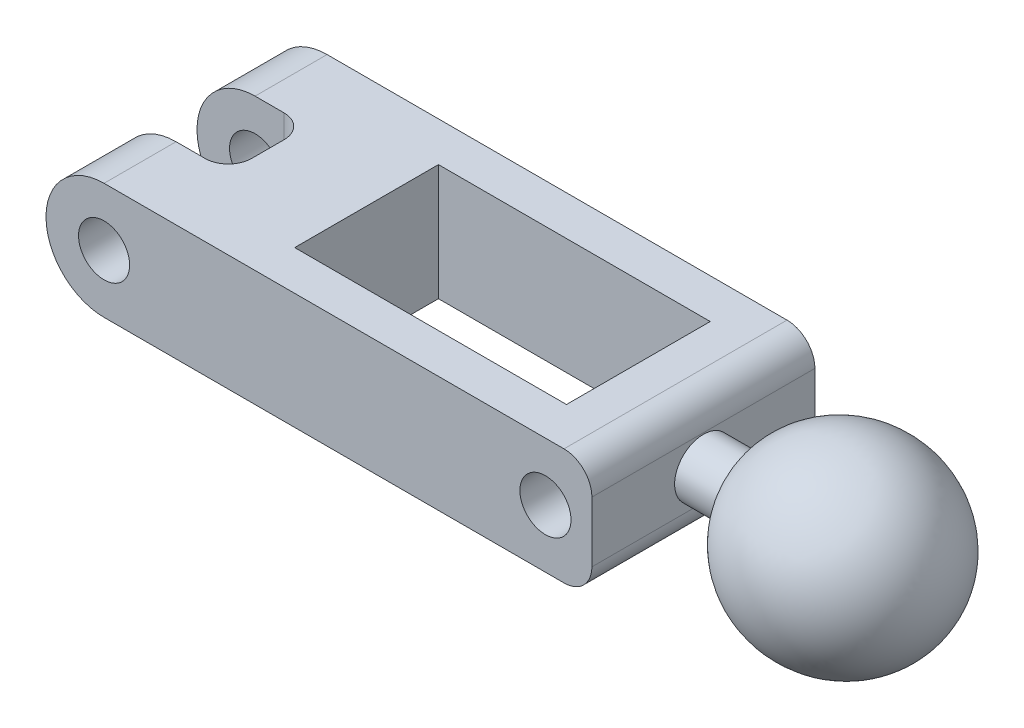
SolidWorks part; units mm, degrees
ref_plane "Front Plane" through (0, 0, 0) normal (0, 0, 1) x (1, 0, 0)
ref_plane "Top Plane" through (0, 0, 0) normal (0, 1, 0) x (1, 0, 0)
ref_plane "Right Plane" through (0, 0, 0) normal (1, 0, 0) x (0, 0, -1)
sketch "Sketch1" plane through (0, 0, 0) normal (0, 0, 1) x (1, 0, 0)
  line L0 (9.5, 0) -> (-9.5, 0) construction
  line L1 (9.5, -2.5) -> (-9.5, -2.5)
  line L2 (9.5, 2.5) -> (-9.5, 2.5)
  line L3 (9.5, 2.5) -> (9.5, -2.5) construction
  line L4 (9.5, 2.5) -> (10.3, 2.5)
  line L5 (11.5, 1.3) -> (11.5, -0.8015)
  line L6 (10.3, -2.5) -> (9.5, -2.5)
  line L9 (11.5, -0.8015) -> (11.5, -1.3)
  arc A1 (-9.5, 2.5) -> (-9.5, -2.5) centre (-9.5, 0) ccw
  circle A2 centre (-9.5, 0) radius 1.1
  circle A3 centre (9.5, 0) radius 1.1
  arc A4 (11.5, -1.3) -> (10.3, -2.5) centre (10.3, -1.3) cw
  arc A5 (10.3, 2.5) -> (11.5, 1.3) centre (10.3, 1.3) cw
  point P2 (0, 0)
  dimension "D1" = 2.5
  dimension "D3" = 2.2
  dimension "D5" = 1.2
  dimension "D2" = 19
  dimension "D4" = 21
extrude "Boss-Extrude1" add sketch "Sketch1" along normal mid plane 9.6
sketch "Sketch2" plane through (0, 0, 0) normal (0, 1, 0) x (1, 0, 0)
  line L0 (-12, 4.8) -> (-12, -4.8) construction
  line L1 (-12, 1.7) -> (-7.25, 1.7)
  line L2 (-12, 1.7) -> (-12, -1.7)
  line L3 (-12, -1.7) -> (-7.25, -1.7)
  line L4 (-7.25, 1.7) -> (-7.25, -1.7)
  line L5 (0, 0) -> (-14.5, 0) construction
  line L7 (-9.5, -4.8) -> (-9.5, 4.8) construction
  line L8 (8.7, 3.094) -> (-3, 3.094)
  line L9 (8.7, 3.094) -> (8.7, -3.094)
  line L10 (8.7, -3.094) -> (-3, -3.094)
  line L11 (-3, 3.094) -> (-3, -3.094)
  line L12 (8.7, 3.094) -> (-3, -3.094) construction
  line L13 (8.7, -3.094) -> (-3, 3.094) construction
  line L14 (-9.5, 4.8) -> (10.3, 4.8) construction
  line L15 (-8.4, 4.8) -> (-10.6, 4.8) construction
  point P9 (-7.25, 0)
  point P12 (2.85, 0)
  dimension "D1" = 4.25
  dimension "D2" = 2.25
  dimension "D3" = 18.2
  dimension "D4" = 7.894
  dimension "D5" = 3.1
extrude "Cut-Extrude1" cut sketch "Sketch2" against normal mid plane 9.6 contours L8 L11 L10 L9 | L1 L4 L3 L2
sketch "Sketch6" plane through (0, 0, 0) normal (0, 0, 1) x (1, 0, 0)
  line L0 (11.5, 1.3) -> (11.5, -1.3) construction
  line L3 (11.5, -1.24) -> (13.5, -1.24)
  line L6 (13.5, 0) -> (21.6962, 0) construction
  line L8 (0, 0) -> (3.0263, 0) construction
  line L9 (11.5, 0) -> (21.6962, 0)
  line L10 (11.5, 0) -> (11.5, -1.24)
  circle A1 centre (-9.5, 0) radius 1.1 construction
  ellipse E0 centre (17.5, -0.0284) end of major axis (21.6962, 0) minor radius 4 (13.5, -1.24) -> (21.6962, 0) ccw
  point P0 (11.5, 0)
  dimension "D3" = 27
  dimension "D1" = 1.24
  dimension "D2" = 2
  dimension "D4" = 8
revolve "Revolve5" add sketch "Sketch6" angle 360 about L9
fillet "Fillet1" radius 1 2 edges at (-7.25, 0, -1.7) (-7.25, 0, 1.7)
